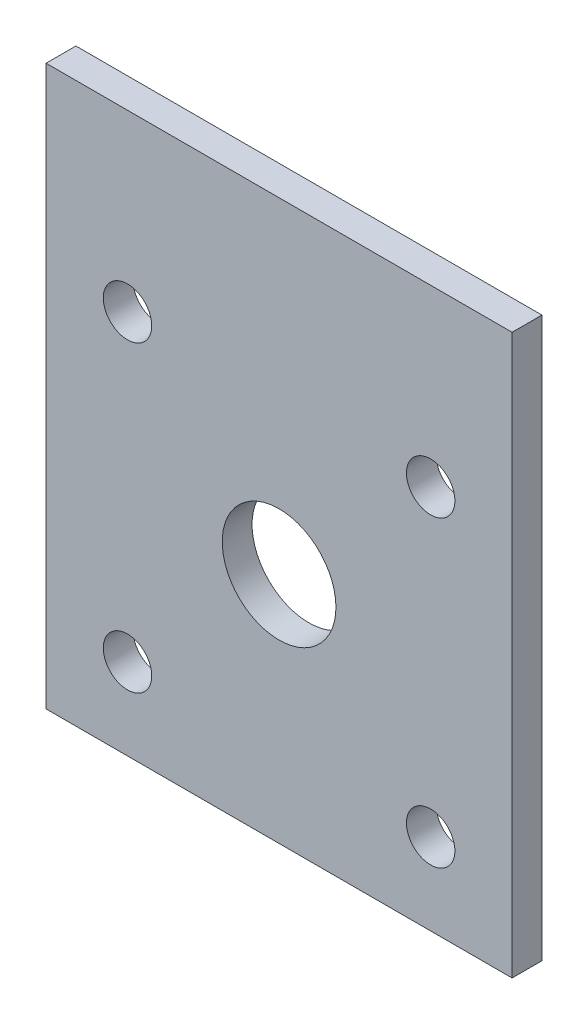
SolidWorks part; units mm, degrees
ref_plane "前视基准面" through (0, 0, 0) normal (0, 0, 1) x (1, 0, 0)
ref_plane "上视基准面" through (0, 0, 0) normal (0, 1, 0) x (1, 0, 0)
ref_plane "右视基准面" through (0, 0, 0) normal (1, 0, 0) x (0, 0, -1)
sketch "草图1" plane through (0, 0, 0) normal (0, 0, 1) x (1, 0, 0)
  line L0 (12.5, 25) -> (12.5, 0) construction
  line L1 (0, 0) -> (25, 0)
  line L2 (0, 0) -> (0, 30)
  line L3 (0, 30) -> (25, 30)
  line L4 (25, 0) -> (25, 30)
  line L5 (0, 12.5) -> (25, 12.5) construction
  line L6 (4.3683, 4.3683) -> (4.3683, 20.6317) construction
  line L7 (4.3683, 20.6317) -> (20.6317, 20.6317) construction
  circle A0 centre (4.3683, 20.6317) radius 1.3
  circle A1 centre (20.6317, 20.6317) radius 1.3
  circle A2 centre (20.6317, 4.3683) radius 1.3
  circle A3 centre (4.3683, 4.3683) radius 1.3
  circle A4 centre (12.5, 12.5) radius 11.5 construction
  circle A5 centre (12.5, 12.5) radius 3.05
  dimension "D3" = 16.2635
  dimension "D4" = 2.6
  dimension "D6" = 23
  dimension "D5" = 6.1
  dimension "D1" = 30
  dimension "D2" = 25
  dimension "D7" = 12.5
extrude "凸台-拉伸1" add sketch "草图1" along normal blind 1.6
